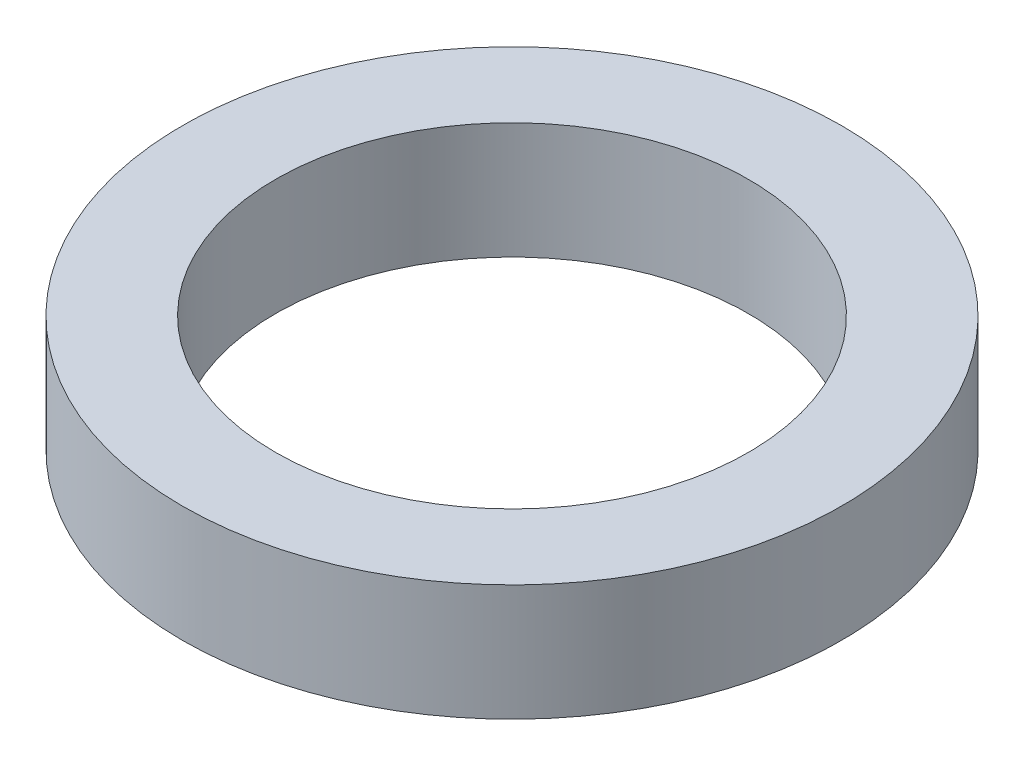
SolidWorks part; units mm, degrees
other "Pivot Bearing Inner Spacer"
ref_plane "Front Plane" through (0, 0, 0) normal (0, 0, 1) x (1, 0, 0)
ref_plane "Top Plane" through (0, 0, 0) normal (0, 1, 0) x (1, 0, 0)
ref_plane "Right Plane" through (0, 0, 0) normal (1, 0, 0) x (0, 0, -1)
sketch3d "Spacer ring sketch datum points"
  point P0 (-56.2917, -136, 0)
  point P1 (-46.2917, -136, 0)
  point P2 (-56.2917, -136, -10)
ref_plane "Spacer ring sketch plane" through (0, -136, 0) normal (0, 1, 0) x (1, 0, 0)
sketch "Spacer ring sketch" plane through (0, -136, 0) normal (0, 1, 0) x (1, 0, 0)
  circle A0 centre (-56.2917, 0) radius 8.5
  circle A1 centre (-56.2917, 0) radius 6.1
extrude "Spacer ring" add sketch "Spacer ring sketch" along normal blind 3 separate body
